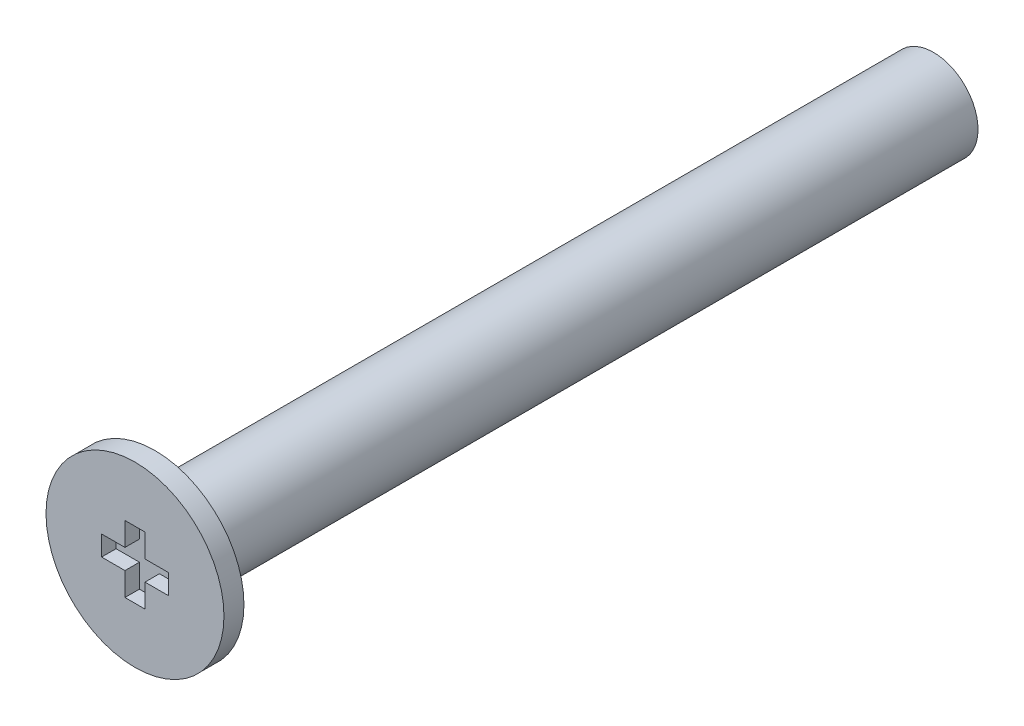
SolidWorks part; units mm, degrees
ref_plane "前视基准面" through (0, 0, 0) normal (0, 0, 1) x (1, 0, 0)
ref_plane "上视基准面" through (0, 0, 0) normal (0, 1, 0) x (1, 0, 0)
ref_plane "右视基准面" through (0, 0, 0) normal (1, 0, 0) x (0, 0, -1)
other "Configuration Table"
sketch "草图1" plane through (0, 0, 0) normal (0, 0, 1) x (1, 0, 0)
  circle A0 centre (0, 0) radius 2
extrude "标准杆径_头下长度" add sketch "草图1" against normal blind 35
sketch "草图2" plane through (0, 0, 0) normal (0, 0, 1) x (1, 0, 0)
  circle A0 centre (0, 0) radius 3.5
sketch "草图4" plane through (0, 0, 0) normal (0, 1, 0) x (1, 0, 0)
  line L0 (0, 0) -> (4.7, 0)
  line L1 (4.7, 0) -> (4.7, -0.2884)
  line L2 (0, -2.5) -> (0, 0)
  line L3 (0, 2) -> (0, -4.5) construction
  arc A0 (4.7, -0.2884) -> (0, -2.5) centre (0, 3.6) cw
sketch "草图5" plane through (0, 0, 0) normal (0, 0, 1) x (1, 0, 0)
  line L0 (-0.5, -2.15) -> (0.5, -2.15)
  line L1 (0.5, -2.15) -> (0.5, -0.5)
  line L2 (0.5, -0.5) -> (2.15, -0.5)
  line L3 (2.15, -0.5) -> (2.15, 0.5)
  line L4 (2.15, 0.5) -> (0.5, 0.5)
  line L5 (0.5, 0.5) -> (0.5, 2.15)
  line L6 (0.5, 2.15) -> (-0.5, 2.15)
  line L7 (-0.5, 2.15) -> (-0.5, 0.5)
  line L8 (-0.5, 0.5) -> (-2.15, 0.5)
  line L9 (-2.15, 0.5) -> (-2.15, -0.5)
  line L10 (-2.15, -0.5) -> (-0.5, -0.5)
  line L11 (-0.5, -0.5) -> (-0.5, -2.15)
sketch "草图6" plane through (0, 0, 0) normal (0, 1, 0) x (1, 0, 0)
  line L0 (0, 0) -> (4, 0)
  line L1 (4, 0) -> (4, -0.9)
  line L2 (4, -0.9) -> (0, -0.9)
  line L3 (0, -0.9) -> (0, 0)
  line L4 (0, 2) -> (0, -2.9) construction
revolve "已确认_十字槽超薄头" add sketch "草图6" angle 360 about L4
sketch "草图7" plane through (0, 0, 0) normal (0, 0, 1) x (1, 0, 0)
  line L0 (-0.45, -1.5) -> (0.45, -1.5)
  line L1 (0.45, -1.5) -> (0.45, -0.45)
  line L2 (0.45, -0.45) -> (1.5, -0.45)
  line L3 (1.5, -0.45) -> (1.5, 0.45)
  line L4 (1.5, 0.45) -> (0.45, 0.45)
  line L5 (0.45, 0.45) -> (0.45, 1.5)
  line L6 (0.45, 1.5) -> (-0.45, 1.5)
  line L7 (-0.45, 1.5) -> (-0.45, 0.45)
  line L8 (-0.45, 0.45) -> (-1.5, 0.45)
  line L9 (-1.5, 0.45) -> (-1.5, -0.45)
  line L10 (-1.5, -0.45) -> (-0.45, -0.45)
  line L11 (-0.45, -0.45) -> (-0.45, -1.5)
extrude "十字槽_PH2_简化" cut sketch "草图7" against normal blind 0.66 from offset 0.91
